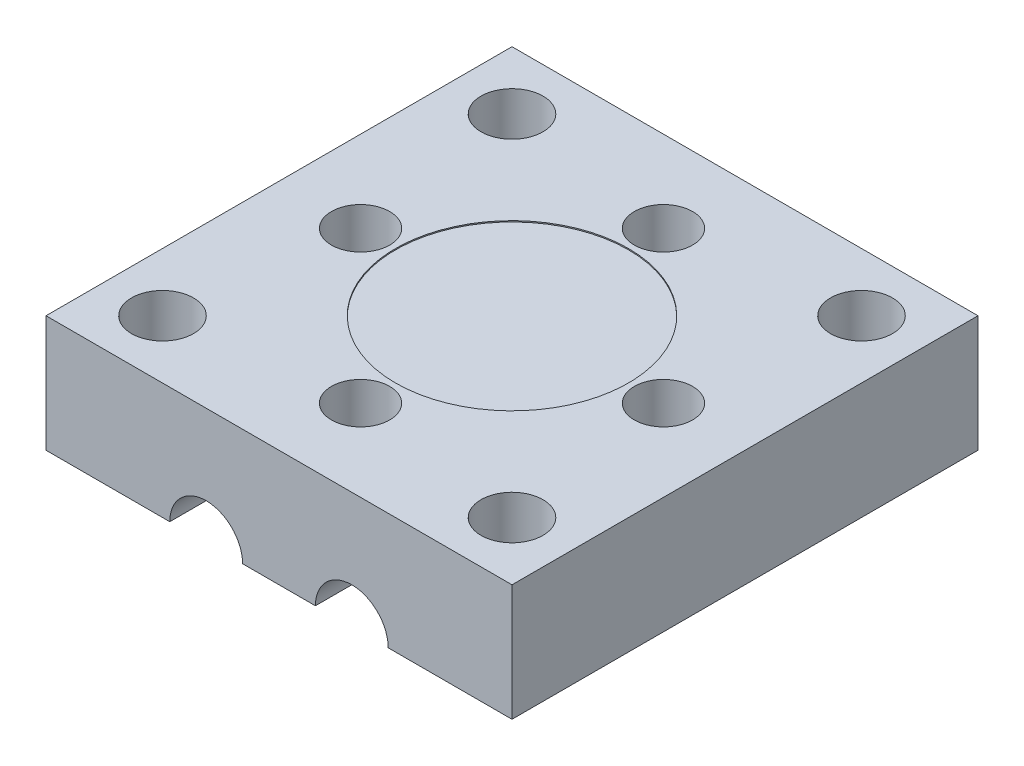
SolidWorks part; units mm, degrees
ref_plane "Front Plane" through (0, 0, 0) normal (0, 0, 1) x (1, 0, 0)
ref_plane "Top Plane" through (0, 0, 0) normal (0, 1, 0) x (1, 0, 0)
ref_plane "Right Plane" through (0, 0, 0) normal (1, 0, 0) x (0, 0, -1)
sketch "Sketch1" plane through (0, 0, 0) normal (0, 1, 0) x (1, 0, 0)
  line L1 (-25.4, 25.4) -> (25.4, 25.4)
  line L2 (-25.4, 25.4) -> (-25.4, -25.4)
  line L3 (-25.4, -25.4) -> (25.4, -25.4)
  line L4 (25.4, 25.4) -> (25.4, -25.4)
  dimension "D1" = 50.8
  dimension "D2" = 50.8
  dimension "D3" = 25.4
  dimension "D4" = 25.4
extrude "Boss-Extrude1" add sketch "Sketch1" along normal blind 12.7
sketch "Sketch2" plane through (0, 0, 25.4) normal (0, 0, 1) x (1, 0, 0)
  line L0 (-25.4, 0) -> (25.4, 0) construction
  circle A0 centre (-7.9375, 0) radius 3.9688
  circle A1 centre (7.9375, 0) radius 3.9688
  dimension "D1" = 7.9375
  dimension "D2" = 7.9375
  dimension "D3" = 7.9375
  dimension "D4" = 7.9375
extrude "Cut-Extrude1" cut sketch "Sketch2" against normal through all
hole_wizard "1/4 Clearance Hole1" positions "Sketch5" profile "Sketch4" hole size "1/4" standard "ANSI Inch" end condition through all
sketch "Sketch5" plane through (0, 12.7, 0) normal (0, 1, 0) x (1, 0, 0)
  point P0 (-19.05, -19.05)
  point P2 (-19.05, 19.05)
  point P4 (19.05, 19.05)
  point P6 (19.05, -19.05)
sketch "Sketch4" plane through (-19.05, 12.7, 19.05) normal (1, 0, 0) x (0, 0, 1)
  line L0 (0, 0) -> (0, 12.7)
  line L1 (0, 12.7) -> (3.3782, 12.7)
  line L2 (3.3782, 12.7) -> (3.3782, 0)
  line L5 (3.3782, 0) -> (0, 0)
  line L11 (0, -6.35) -> (0, 107.95) construction
  dimension "Thru Hole Dia." = 6.7564
  dimension "Thru Hole Depth" = 12.7
sketch "Sketch7" plane through (0, 12.7, 0) normal (0, 1, 0) x (1, 0, 0)
  line L0 (25.4, -25.4) -> (25.4, 25.4) construction
  line L1 (25.4, 25.4) -> (-25.4, 25.4) construction
  circle A0 centre (-16.51, 0) radius 3.175
  circle A1 centre (0, 16.51) radius 3.175
  circle A2 centre (16.51, 0) radius 3.175
  circle A3 centre (0, -16.51) radius 3.175
  circle A4 centre (19.05, -19.05) radius 3.3782 construction
  dimension "D2" = 6.35
  dimension "D1" = 16.51
  dimension "D3" = 16.51
  dimension "D4" = 16.51
  dimension "D5" = 16.51
  dimension "D6" = 25.4
  dimension "D7" = 25.4
extrude "Cut-Extrude2" cut sketch "Sketch7" against normal blind 6.35
hole_wizard "#6 Clearance Hole1" positions "Sketch14" profile "Sketch13" hole size "#6" standard "ANSI Inch" end condition through all
sketch "Sketch14" plane through (0, 6.35, 0) normal (0, 1, 0) x (1, 0, 0)
  point P0 (-16.51, 0)
  point P2 (0, 16.51)
  point P5 (16.51, 0)
  point P8 (0, -16.51)
sketch "Sketch13" plane through (-16.51, 6.35, 0) normal (1, 0, 0) x (0, 0, 1)
  line L0 (0, 0) -> (0, 6.35)
  line L1 (0, 6.35) -> (1.8986, 6.35)
  line L2 (1.8986, 6.35) -> (1.8986, 0)
  line L5 (1.8986, 0) -> (0, 0)
  line L11 (0, -6.35) -> (0, 107.95) construction
  dimension "Thru Hole Dia." = 3.7973
  dimension "Thru Hole Depth" = 6.35
sketch "Sketch15" plane through (0, 0, 0) normal (0, -1, 0) x (1, 0, 0)
  circle A0 centre (0, 16.51) radius 3.175
  circle A1 centre (16.51, 0) radius 3.175
  circle A2 centre (0, -16.51) radius 3.175
  circle A3 centre (-16.51, 0) radius 3.175
  dimension "D1" = 6.35
extrude "Cut-Extrude5" cut sketch "Sketch15" against normal blind 1.5875
sketch "Sketch16" plane through (0, 12.7, 0) normal (0, 1, 0) x (1, 0, 0)
  circle A0 centre (0, 0) radius 12.7
extrude "Cut-Extrude6" cut sketch "Sketch16" against normal blind 0.127
